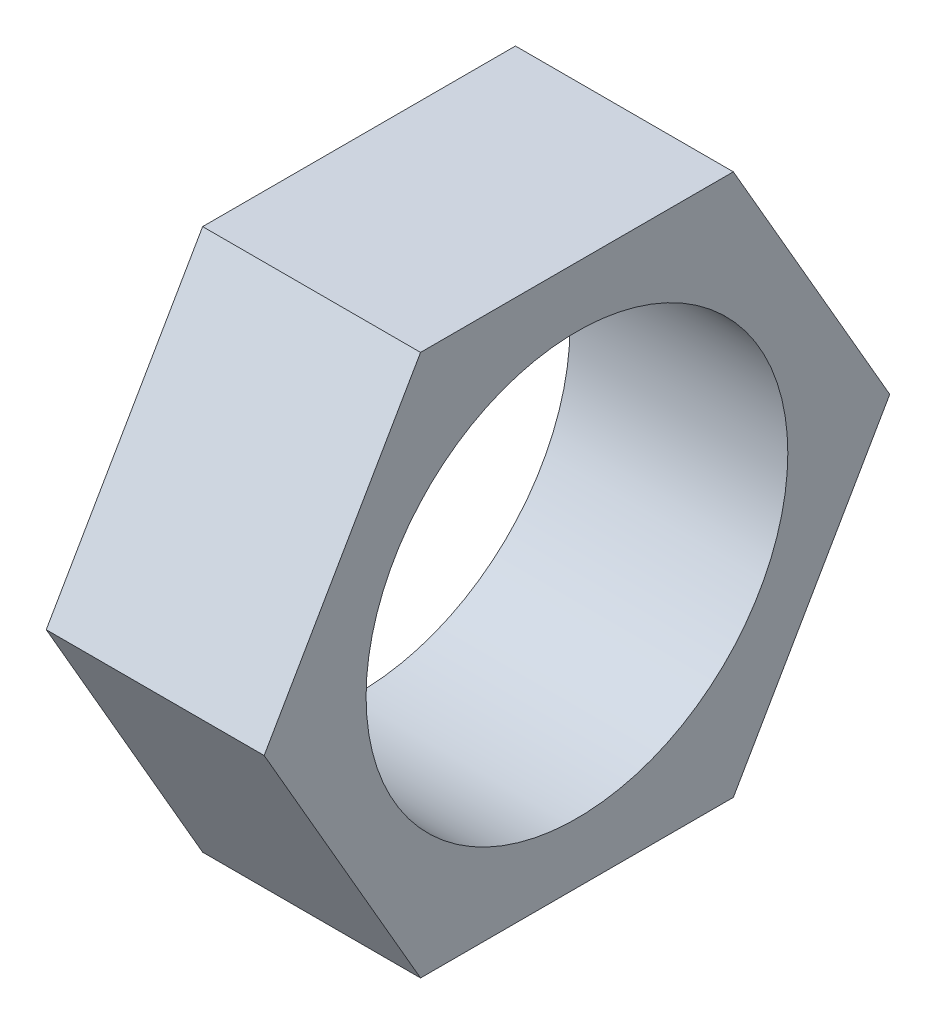
SolidWorks part; units mm, degrees
ref_plane "前视基准面" through (0, 0, 0) normal (0, 0, 1) x (1, 0, 0)
ref_plane "上视基准面" through (0, 0, 0) normal (0, 1, 0) x (1, 0, 0)
ref_plane "右视基准面" through (0, 0, 0) normal (1, 0, 0) x (0, 0, -1)
sketch "草图1" plane through (0, 0, 0) normal (1, 0, 0) x (0, 0, -1)
  line L0 (4.45, 0) -> (2.225, 3.8538)
  line L1 (2.225, -3.8538) -> (4.45, 0)
  line L2 (-2.225, -3.8538) -> (2.225, -3.8538)
  line L3 (-4.45, 0) -> (-2.225, -3.8538)
  line L4 (-2.225, 3.8538) -> (-4.45, 0)
  line L5 (2.225, 3.8538) -> (-2.225, 3.8538)
  dimension "D1" = 6
extrude "凸台-拉伸1" add sketch "草图1" along normal blind 3.1
sketch "草图2" plane through (3.1, 0, 0) normal (1, 0, 0) x (0, 0, -1)
  circle A0 centre (0, 0) radius 3
extrude "切除-拉伸1" cut sketch "草图2" against normal through all
